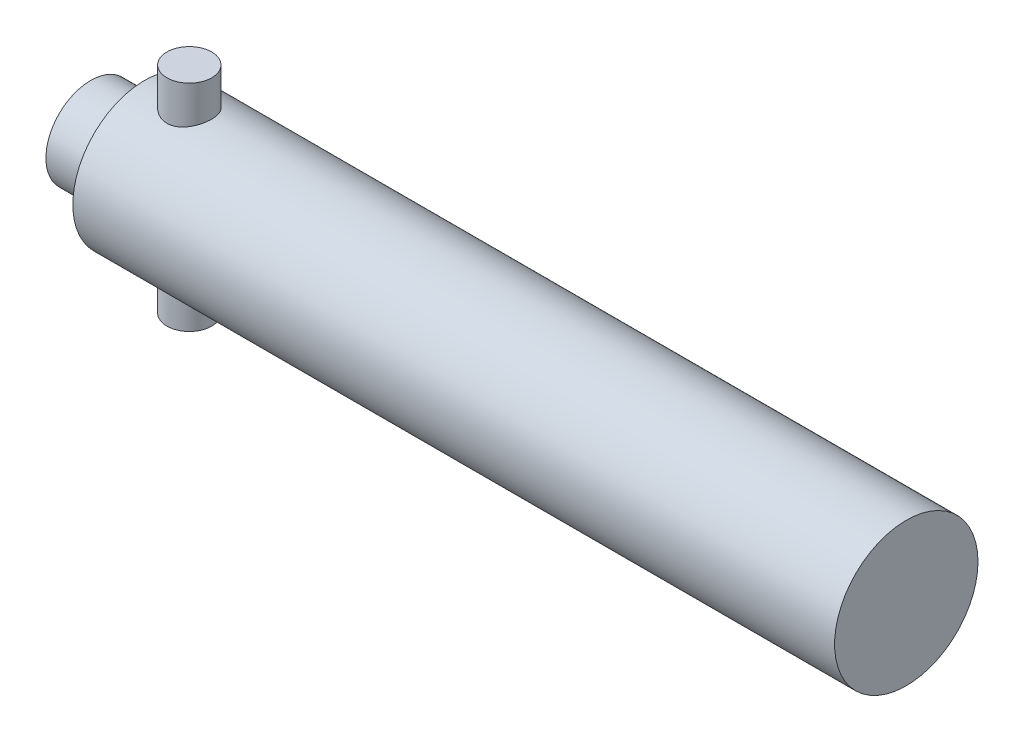
SolidWorks part; units mm, degrees
ref_plane "Front Plane" through (0, 0, 0) normal (0, 0, 1) x (1, 0, 0)
ref_plane "Top Plane" through (0, 0, 0) normal (0, 1, 0) x (1, 0, 0)
ref_plane "Right Plane" through (0, 0, 0) normal (1, 0, 0) x (0, 0, -1)
sketch "Sketch1" plane through (0, 0, 0) normal (1, 0, 0) x (0, 0, -1)
  circle A0 centre (0, 0) radius 101.6
  dimension "D1" = 203.2
extrude "Boss-Extrude1" add sketch "Sketch1" along normal mid plane 1079.5
sketch "Sketch2" plane through (0, 0, 0) normal (0, 1, 0) x (1, 0, 0)
  line L0 (-539.75, 101.6) -> (-539.75, -101.6) construction
  circle A0 centre (-476.25, 0) radius 31.75
  dimension "D1" = 63.5
  dimension "D2" = 63.5
extrude "Boss-Extrude2" add sketch "Sketch2" along normal mid plane 304.8
sketch "Sketch3" plane through (-539.75, 0, 0) normal (-1, 0, 0) x (0, 0, 1)
  circle A0 centre (0, 0) radius 63.5
  dimension "D1" = 127
extrude "Boss-Extrude3" add sketch "Sketch3" along normal blind 76.2
